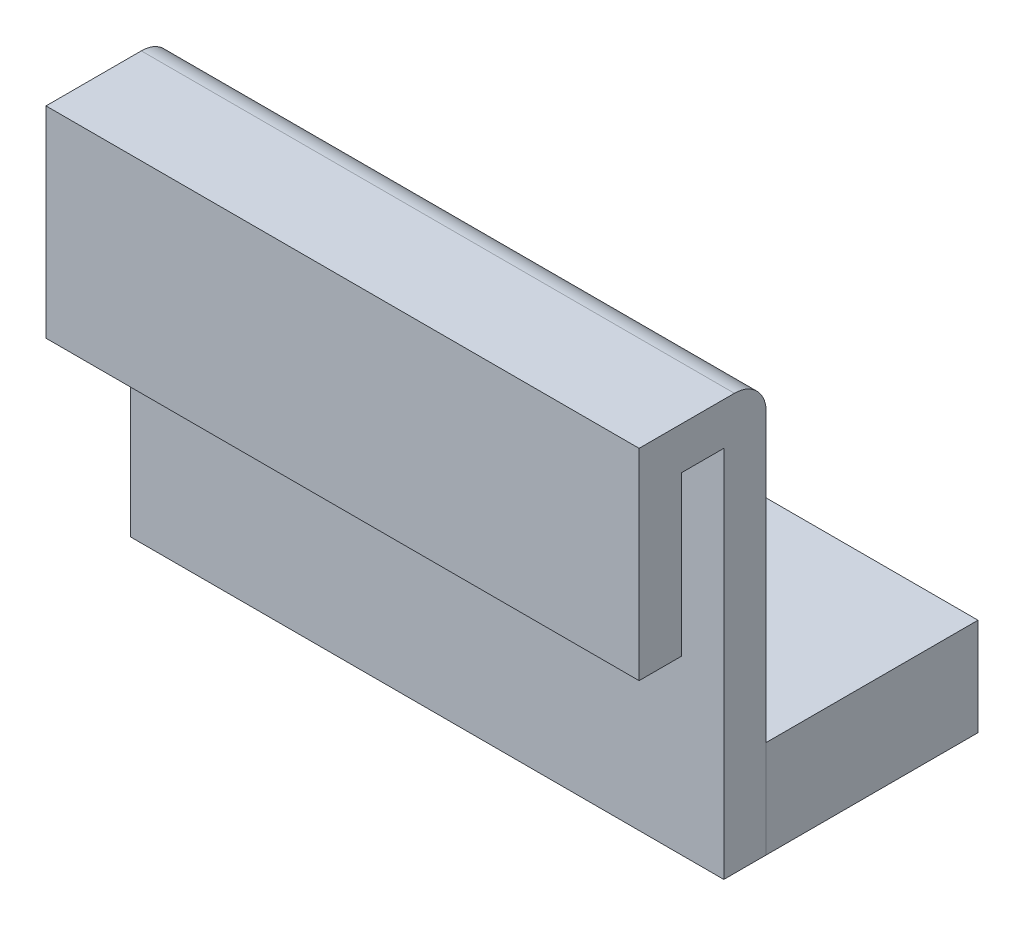
SolidWorks part; units mm, degrees
ref_plane "Front Plane" through (0, 0, 0) normal (0, 0, 1) x (1, 0, 0)
ref_plane "Top Plane" through (0, 0, 0) normal (0, 1, 0) x (1, 0, 0)
ref_plane "Right Plane" through (0, 0, 0) normal (1, 0, 0) x (0, 0, -1)
sketch "Sketch1" plane through (0, 0, 0) normal (0, 0, 1) x (1, 0, 0)
  line L1 (-280, 46) -> (280, 46)
  line L2 (-280, 46) -> (-280, -46)
  line L3 (-280, -46) -> (280, -46)
  line L4 (280, 46) -> (280, -46)
  line L5 (-280, 46) -> (280, -46) construction
  line L6 (-280, -46) -> (280, 46) construction
  point P0 (0, 0)
  dimension "D1" = 560
  dimension "D2" = 92
extrude "Boss-Extrude1" add sketch "Sketch1" along normal blind 200
sketch "Sketch2" plane through (0, 0, 200) normal (0, 0, 1) x (1, 0, 0)
  line L1 (-280, -46) -> (280, -46)
  line L2 (-280, -46) -> (-280, 306.56)
  line L3 (-280, 306.56) -> (280, 306.56)
  line L4 (280, -46) -> (280, 306.56)
  dimension "D1" = 352.56
extrude "Boss-Extrude2" add sketch "Sketch2" along normal blind 40 separate body
sketch "Sketch3" plane through (0, 0, 0) normal (0, 0, -1) x (-1, 0, 0)
  circle A0 centre (0, 0) radius 15
  dimension "D1" = 30
extrude "Cut-Extrude1" cut sketch "Sketch3" against normal blind 5 and the other way through all
sketch "Sketch4" plane through (0, 306.56, 0) normal (0, 1, 0) x (1, 0, 0)
  line L1 (-280, -200) -> (280, -200)
  line L2 (-280, -200) -> (-280, -240)
  line L3 (-280, -240) -> (280, -240)
  line L4 (280, -200) -> (280, -240)
extrude "Boss-Extrude3" add sketch "Sketch4" along normal blind 40
sketch "Sketch5" plane through (0, 0, 240) normal (0, 0, 1) x (1, 0, 0)
  line L0 (280, -46) -> (280, 346.56) construction
  line L1 (-280, 346.56) -> (280, 346.56)
  line L2 (-280, 346.56) -> (-280, 306.56)
  line L3 (-280, 306.56) -> (280, 306.56)
  line L4 (280, 346.56) -> (280, 306.56)
  dimension "D1" = 40
extrude "Boss-Extrude4" add sketch "Sketch5" along normal blind 40
fillet "Fillet1" radius 30 1 edges at (0, 346.56, 200)
sketch "Sketch6" plane through (0, 0, 280) normal (0, 0, 1) x (1, 0, 0)
  line L1 (-280, 346.56) -> (280, 346.56)
  line L2 (-280, 346.56) -> (-280, 306.56)
  line L3 (-280, 306.56) -> (280, 306.56)
  line L4 (280, 346.56) -> (280, 306.56)
extrude "Boss-Extrude5" add sketch "Sketch6" along normal blind 40
sketch "Sketch7" plane through (0, 306.56, 0) normal (0, -1, 0) x (1, 0, 0)
  line L0 (280, 320) -> (280, 240) construction
  line L1 (-280, 320) -> (280, 320)
  line L2 (-280, 320) -> (-280, 280)
  line L3 (-280, 280) -> (280, 280)
  line L4 (280, 320) -> (280, 280)
extrude "Boss-Extrude6" add sketch "Sketch7" along normal blind 150
